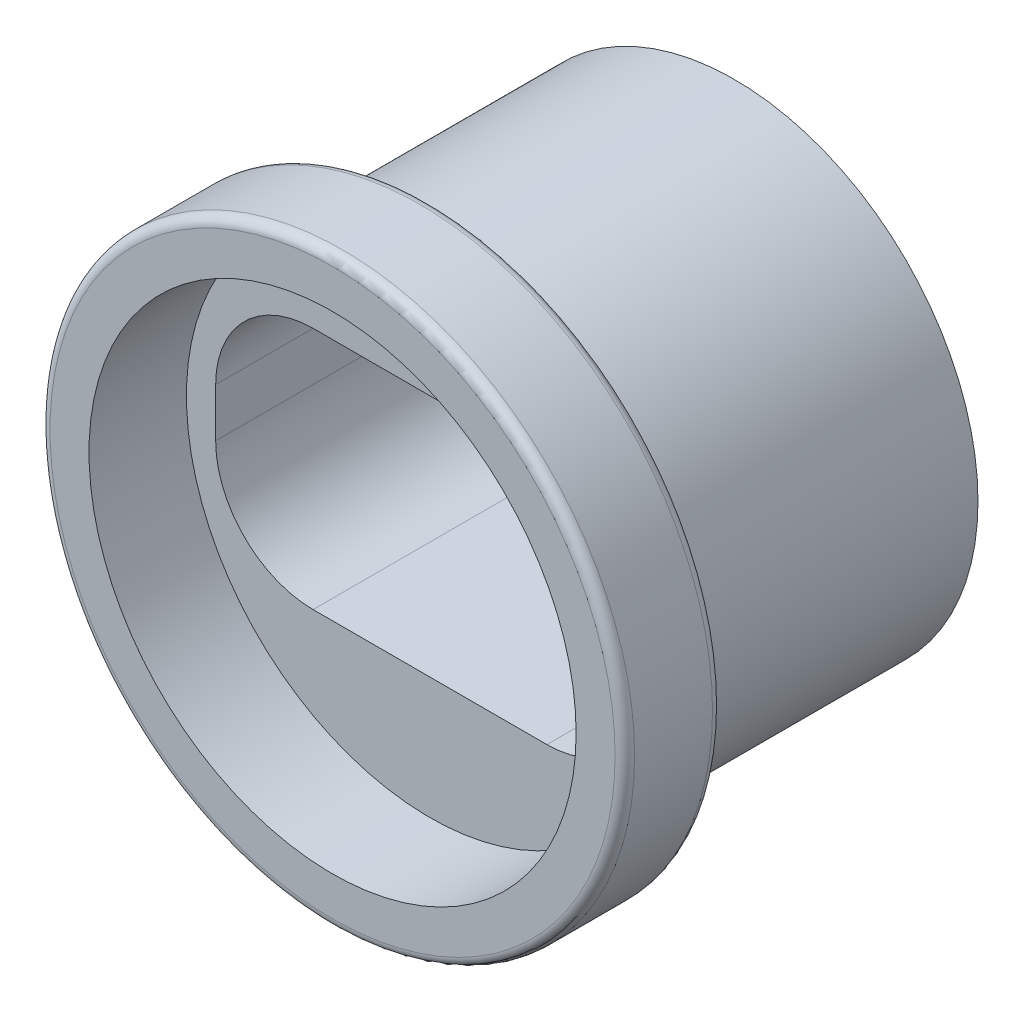
SolidWorks part; units mm, degrees
ref_plane "Front Plane" through (0, 0, 0) normal (0, 0, 1) x (1, 0, 0)
ref_plane "Top Plane" through (0, 0, 0) normal (0, 1, 0) x (1, 0, 0)
ref_plane "Right Plane" through (0, 0, 0) normal (1, 0, 0) x (0, 0, -1)
sketch "Sketch1" plane through (0, 0, 0) normal (0, 0, 1) x (1, 0, 0)
  line L1 (3.048, -3.175) -> (-3.048, -3.175)
  line L2 (5.588, -0.635) -> (5.588, 0.635)
  line L3 (3.048, 3.175) -> (-3.048, 3.175)
  line L4 (-5.588, -0.635) -> (-5.588, 0.635)
  line L5 (5.588, -3.175) -> (-5.588, 3.175) construction
  line L6 (5.588, 3.175) -> (-5.588, -3.175) construction
  circle A0 centre (0, 0) radius 6.35
  arc A1 (5.588, 0.635) -> (3.048, 3.175) centre (3.048, 0.635) ccw
  arc A2 (5.588, -0.635) -> (3.048, -3.175) centre (3.048, -0.635) cw
  arc A3 (-3.048, -3.175) -> (-5.588, -0.635) centre (-3.048, -0.635) cw
  arc A4 (-5.588, 0.635) -> (-3.048, 3.175) centre (-3.048, 0.635) cw
  dimension "D1" = 12.7
  dimension "D4" = 2.54
  dimension "D2" = 11.176
  dimension "D3" = 6.35
extrude "Boss-Extrude1" add sketch "Sketch1" along normal blind 7.9375
sketch "Sketch2" plane through (0, 0, 7.9375) normal (0, 0, 1) x (1, 0, 0)
  circle A0 centre (0, 0) radius 6.35
  circle A1 centre (0, 0) radius 7.62
  circle A2 centre (0, 0) radius 6.35 construction
  dimension "D1" = 15.24
extrude "Boss-Extrude2" add sketch "Sketch2" along normal blind 2.54 separate body
fillet "Fillet1" radius 0.254 2 edges at (7.62, 0, 10.4775) (7.62, 0, 7.9375)
